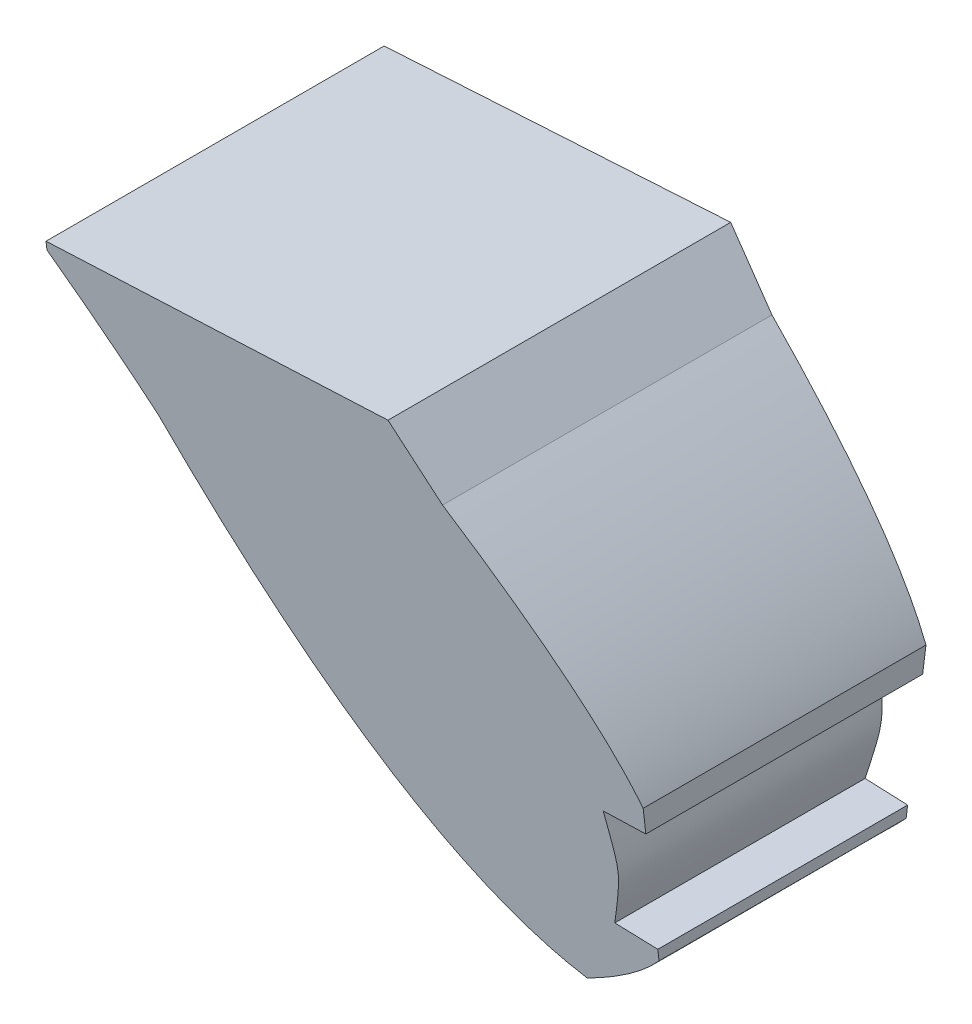
SolidWorks part; units mm, degrees
ref_plane "Alzado" through (0, 0, 0) normal (0, 0, 1) x (1, 0, 0)
ref_plane "Planta" through (0, 0, 0) normal (0, 1, 0) x (1, 0, 0)
ref_plane "Vista lateral" through (0, 0, 0) normal (1, 0, 0) x (0, 0, -1)
sketch "Croquis1" plane through (0, 0, 0) normal (0, 0, 1) x (1, 0, 0)
  line L0 (-8.9818, 12.6082) -> (-23.0359, 11.8716) construction
  line L1 (-8.9818, 12.6082) -> (-23.0359, 11.8716)
  line L2 (-8.9818, 12.6082) -> (-23.0359, 11.8716) construction
  line L4 (-8.9818, 12.6082) -> (-23.0359, 11.8716)
  line L6 (-1.3949, 1.9763) -> (0.3551, 2.2848) construction
  line L7 (-1.3949, 1.9763) -> (0.3551, 2.2848)
  line L8 (0.3551, 2.2848) -> (0.3551, 2.8423) construction
  line L9 (0.3551, 2.2848) -> (0.3551, 3.0015)
  line L10 (0.3551, -2.2848) -> (-1.3949, -2.2237) construction
  line L11 (0.3551, -2.2848) -> (-1.3949, -2.2237)
  line L12 (0.3551, 2.2848) -> (0.3551, -2.2848) construction
  line L13 (0.3551, -2.2848) -> (0.3551, -2.7233)
  line L14 (-8.9818, 12.6082) -> (-6.9949, 10.4774)
  line L15 (-23.0359, 11.5401) -> (-23.0359, 11.8716) construction
  line L16 (-23.0359, 11.5401) -> (-23.0359, 11.8716)
  arc A0 (-18.9452, 7.5409) -> (-23.0359, 11.5401) centre (-69.8841, -40.4718) ccw construction
  arc A1 (-18.9452, 7.5409) -> (-23.0359, 11.5401) centre (-69.8841, -40.4718) ccw
  spline S1 degree 2 poles (-828.7061, 3922.2202) (545.889, -3962.7836) (-262.0834, 3982.5902) knots 0.462185 0.462185 0.462185 0.537731 0.537731 0.537731 weights 1 1 1 only from (-18.9452, 7.5409) to (-2.8466, -5.0591) construction
  spline S2 degree 2 poles (-18.9452, 7.5409) (-10.215, -3.6976) (-2.8466, -5.0591) knots 0.497667 0.497667 0.497667 0.499554 0.499554 0.499554 weights 1 1 1
  spline S3 degree 2 poles (-3804.8689, 1232.5771) (3762.9122, -1369.6643) (-3716.5752, 1504.852) knots 0.462212 0.462212 0.462212 0.537836 0.537836 0.537836 weights 1 1 1 only from (0.3551, 3.0015) to (-6.9949, 10.4774) construction
  spline S4 degree 2 poles (0.3551, 3.0015) (-1.4487, 6.0584) (-6.9949, 10.4774) knots 0.500821 0.500821 0.500821 0.502013 0.502013 0.502013 weights 1 1 1
  spline S5 degree 2 poles (-1.3949, -2.2237) (-0.9075, -0.1237) (-1.3949, 1.9763) knots 0 0 0 1 1 1 weights 1 3.231801 1 construction
  spline S6 degree 2 poles (-1.3949, -2.2237) (-0.9075, -0.1237) (-1.3949, 1.9763) knots 0 0 0 1 1 1 weights 1 3.231801 1
  spline S7 degree 2 poles (-3997.263, 185.0077) (3984.2333, -348.7483) (-3965.0625, 511.2595) knots 0.462205 0.462205 0.462205 0.537778 0.537778 0.537778 weights 1 1 1 only from (-2.8466, -5.0591) to (0.3551, -2.7233) construction
  spline S8 degree 2 poles (-2.8466, -5.0591) (-0.7424, -3.9352) (0.3551, -2.7233) knots 0.498812 0.498812 0.498812 0.499413 0.499413 0.499413 weights 1 1 1
extrude "Saliente-Extruir1" add sketch "Croquis1" along normal mid plane 14 contours S2 S8 L13 L11 S6 L7 L9 S4 L14 L1 L16 A1
sketch "Croquis3" plane through (0, 0, 0) normal (0, 0, 1) x (1, 0, 0)
  line L0 (-6.742, 0) -> (0, 0) construction
  line L1 (-1.8181, 2) -> (-1.7771, 2.0103) construction
  line L3 (-1.8181, 2) -> (-0.1689, 2.4155) construction
  line L4 (-1.8181, 2) -> (0.3551, 3.0015)
  line L5 (0.3551, 3.0015) -> (0.3551, 0)
  line L6 (-1.9135, -2.1825) -> (0.3551, -2.2848)
  line L7 (0.3551, -2.2848) -> (0.3551, 0)
  parabola Q0 (-1.9135, -2.1825) -> (-1.8181, 2) focus (-3.3181, 0) apex (-1.3181, 0)
  dimension "D1" = 2
  dimension "D2" = 2
extrude "Cortar-Extruir1" [suppressed] cut sketch "Croquis3" against normal through all both and the other way through all
sketch "Croquis4" plane through (0, 0, 0) normal (0, 0, 1) x (1, 0, 0)
  line L0 (-1.3949, 1.9763) -> (0.3551, 2.2848) construction
  line L1 (-1.3949, 1.9763) -> (0.3551, 2.2848)
  line L2 (0.3551, 2.2848) -> (0.3551, 3.0015) construction
  line L3 (0.3551, 2.0374) -> (0.3551, 2.2848)
  line L4 (-1.3949, 1.9763) -> (0.3551, 2.0374)
  line L5 (0, 0) -> (-3.4665, 0) construction
  dimension "D1" = 2
extrude "Saliente-Extruir2" add sketch "Croquis4" along normal through all and the other way through all
sketch "Croquis7" plane through (0, 0, 0) normal (0, 0, 1) x (1, 0, 0)
  line L0 (0, 0) -> (-15.3945, 3.3171) construction
  line L1 (-17.3963, 18.9371) -> (-15.3945, 3.3171) construction
  line L2 (-15.3945, 3.3171) -> (-9.9316, -2.6296) construction
  line L3 (-15.3945, 3.3171) -> (-10.2385, 8.0535) construction
  line L4 (-17.3963, 18.9371) -> (-16.5429, 12.2783) construction
  line L5 (0, 0) -> (-1.3461, -2.2254) construction
  line L6 (-69.8841, 29.5282) -> (-81.9382, 42.5765) construction
  line L7 (-69.8841, 29.5282) -> (-20.9497, 29.5282) construction
  line L8 (-17.8101, 13.1658) -> (-25.5429, 13.1658)
  line L9 (-18.2059, 7.0951) -> (-21.9246, 11.9299) construction
  line L10 (0.3551, -2.5) -> (-2.4497, -2.0473)
  line L11 (-1.3461, -2.2254) -> (-2.0075, -3.6222) construction
  line L12 (-1.3461, -2.2254) -> (-1.4547, -2.8987) construction
  line L13 (-1.3461, -2.2254) -> (-1.2286, -1.4976) construction
  line L14 (0.3551, -2.2848) -> (0.3551, -2.7233) construction
  line L15 (0.3551, -2.2848) -> (-1.3949, -2.2237) construction
  line L16 (-2.0075, -3.6222) -> (-3.0629, -5.8512) construction
  line L17 (-2.6331, -4.9434) -> (-3.7044, -5.5324) construction
  line L18 (-2.6331, -4.9434) -> (-3.2248, -3.867) construction
  line L19 (-2.6331, -4.9434) -> (-2.2174, -6.1341) construction
  line L20 (-4.0838, -4.7637) -> (-1.6363, -5.0668) construction
  line L21 (-4.0838, -4.7637) -> (-0.036, -5.9454) construction
  line L22 (-4.0838, -4.7637) -> (-3.7621, -3.6616) construction
  line L23 (-4.0838, -4.7637) -> (-6.31, -3.7023) construction
  line L24 (-6.31, -3.7023) -> (-8.69, -2.5677) construction
  line L25 (-8.69, -2.5677) -> (-6.8421, -3.7725) construction
  line L26 (-8.69, -2.5677) -> (-7.9481, -1.4297) construction
  line L27 (-10.6884, -0.8477) -> (-8.69, -2.5677) construction
  line L28 (-10.6884, -0.8477) -> (-14.8546, 2.738) construction
  line L29 (-14.8546, 2.738) -> (-14.5337, 2.3989) construction
  line L30 (-14.8546, 2.738) -> (-14.6199, 2.9602) construction
  line L31 (-18.2059, 7.0951) -> (-14.8546, 2.738) construction
  line L32 (-8.9818, 12.6082) -> (-23.0359, 11.8716) construction
  line L33 (-8.9818, 12.6082) -> (-23.0359, 11.8716)
  line L34 (-21.9246, 11.9299) -> (-21.9826, 13.0367) construction
  line L35 (-21.9246, 11.9299) -> (-23.4156, 13.0367) construction
  arc A0 (-18.9452, 7.5409) -> (-23.0359, 11.5401) centre (-69.8841, -40.4718) ccw construction
  spline S0 degree 2 poles (-654.4568, 2937.5195) (409.3679, -2972.9237) (-163.476, 2987.5518) knots 0.467242 0.467242 0.467242 0.532662 0.532662 0.532662 weights 1 1 1 only from (-18.9452, 7.5409) to (-2.8466, -5.0591) construction
  spline S1 degree 2 poles (-18.6263, 7.1332) (-10.0803, -3.7225) (-2.8466, -5.0591) knots 0.497702 0.497702 0.497702 0.499554 0.499554 0.499554 weights 1 1 1 construction
  spline S3 degree 2 poles (-2999.4042, 119.7504) (2988.2948, -261.6206) (-2971.0465, 402.239) knots 0.467267 0.467267 0.467267 0.532713 0.532713 0.532713 weights 1 1 1 only from (-2.8466, -5.0591) to (0.3551, -2.7233) construction
  spline S4 degree 2 poles (-2.8466, -5.0591) (-2.7385, -5.0013) (-2.6331, -4.9434) knots 0.498812 0.498812 0.498812 0.498843 0.498843 0.498843 weights 1 1 1
  dimension "D1" = 2.5
  dimension "D2" = 22
  dimension "D3" = 16.17
  dimension "D4" = 54.138
  dimension "D5" = 34.566
  dimension "D6" = 50.413
sketch "Croquis6" plane through (0, 0, 0) normal (1, 0, 0) x (0, 0, -1)
  line L0 (7, 12.6082) -> (7, 10.4774) construction
  line L1 (7, 12.6082) -> (7, -5.0591)
  line L2 (-7, 12.6082) -> (-7, 10.4774) construction
  line L3 (-7, 12.6082) -> (-7, -5.0591)
  line L4 (-7, -5.0591) -> (7, -5.0591) construction
  line L5 (-7, -5.0591) -> (-5, -5.0591)
  line L6 (7, 12.6082) -> (4.5, -5.0591)
  line L7 (-7, 12.6082) -> (-5, -5.0591)
  line L8 (4.5, -5.0591) -> (7, -5.0591)
  dimension "D1" = 2
  dimension "D2" = 2.5
extrude "Cortar-Extruir2" cut sketch "Croquis6" against normal through all and the other way through all
